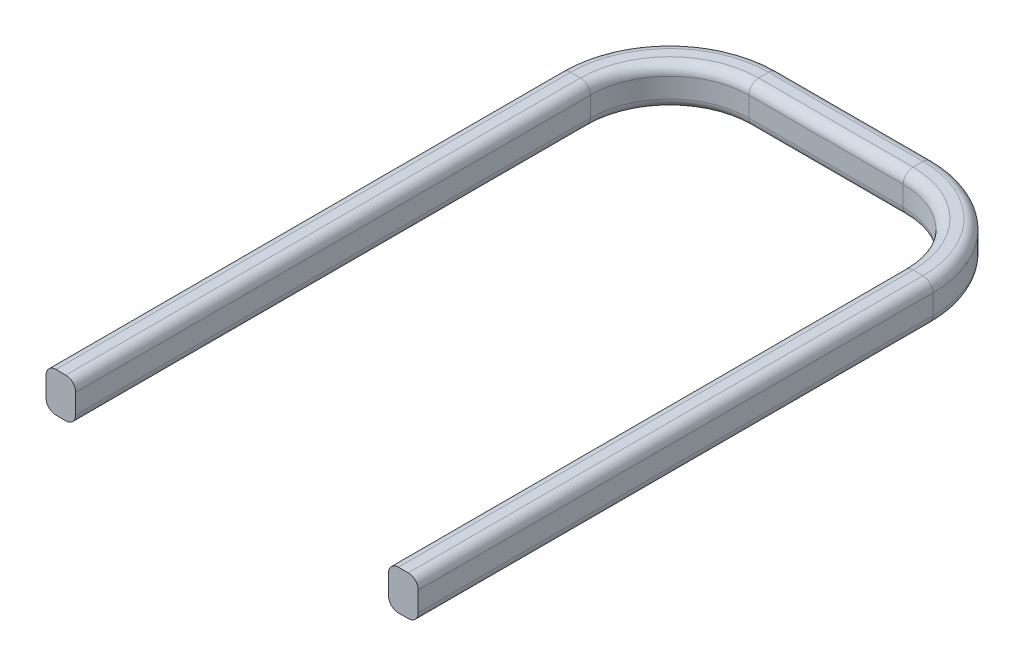
SolidWorks part; units mm, degrees
ref_plane "Front Plane" through (0, 0, 0) normal (0, 0, 1) x (1, 0, 0)
ref_plane "Top Plane" through (0, 0, 0) normal (0, 1, 0) x (1, 0, 0)
ref_plane "Right Plane" through (0, 0, 0) normal (1, 0, 0) x (0, 0, -1)
sketch "Sketch1" plane through (0, 0, 0) normal (0, 1, 0) x (1, 0, 0)
  line L0 (-3.95, 0) -> (-3.95, 13)
  line L1 (-1.95, 15) -> (1.95, 15)
  line L2 (3.95, 13) -> (3.95, 0)
  arc A0 (1.95, 15) -> (3.95, 13) centre (1.95, 13) cw
  arc A1 (-3.95, 13) -> (-1.95, 15) centre (-1.95, 13) cw
  point P5 (0, 15)
  point P11 (-3.95, 15)
  dimension "D3" = 2
  dimension "D1" = 3.95
  dimension "D2" = 15
sketch "Sketch2" plane through (0, 0, 0) normal (0, 0, 1) x (1, 0, 0)
  line L1 (-3.95, 0) -> (-4.7, 0)
  line L2 (-3.95, 0) -> (-3.95, 1)
  line L3 (-3.95, 1) -> (-4.7, 1)
  line L4 (-4.7, 0) -> (-4.7, 1)
  dimension "D1" = 0.75
  dimension "D2" = 1
sweep "Sweep1" add profiles "Sketch2" path "Sketch1"
fillet "Fillet2" radius 0.25 20 edges at (-3.3642, 0, -14.4142) (0, 0, -15) (3.3642, 0, -14.4142) (3.95, 0, -6.5) (4.7, 0, -6.5) (3.8945, 0, -14.9445) (0, 0, -15.75) (-3.8945, 0, -14.9445) (-4.7, 0, -6.5) (-3.95, 0, -6.5) (-4.7, 1, -6.5) (-3.8945, 1, -14.9445) (0, 1, -15.75) (3.8945, 1, -14.9445) (4.7, 1, -6.5) (3.95, 1, -6.5) (3.3642, 1, -14.4142) (0, 1, -15) (-3.3642, 1, -14.4142) (-3.95, 1, -6.5)
